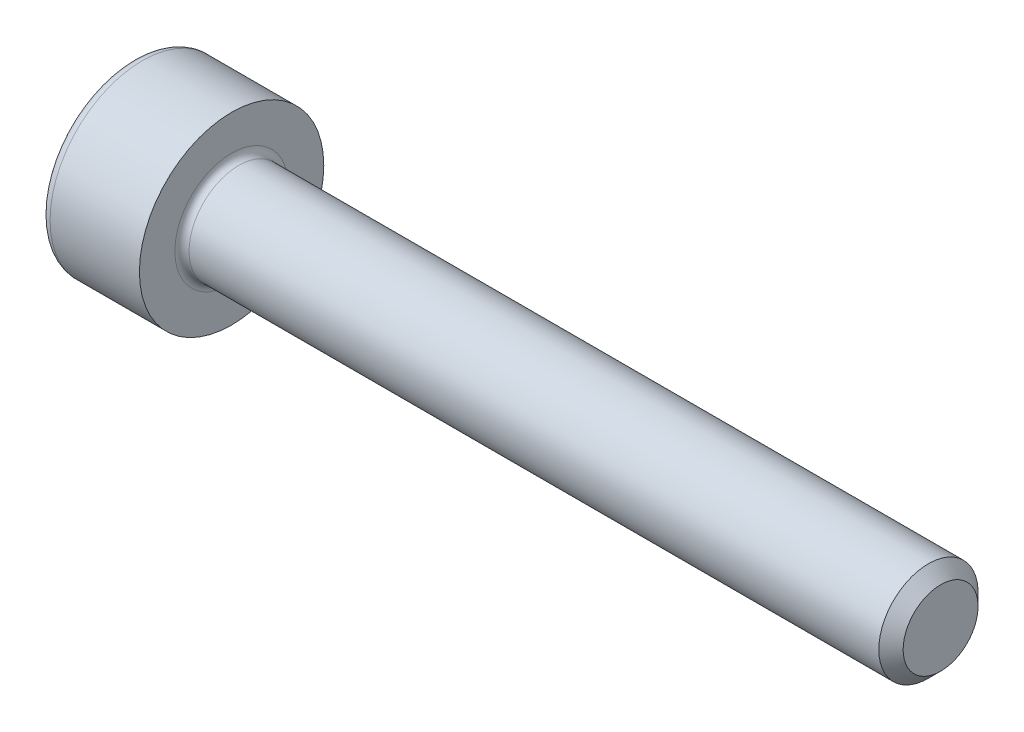
SolidWorks part; units mm, degrees
revolve "Base-Revolve" add sketch "BodySke"
sketch "BodySke" plane through (0, 0, 0) normal (0, 0, 1) x (1, 0, 0)
  line L0 (0, 0) -> (0, 1.3)
  line L1 (0, 1.3) -> (1.4, 1.3)
  line L2 (1.4, 1.3) -> (1.4, 0.7)
  line L3 (1.4, 0.7) -> (11.2285, 0.7)
  line L4 (11.4, 0.5285) -> (11.4, 0)
  line L5 (11.4, 0) -> (0, 0)
  line L6 (-31.75, 0) -> (127, 0) construction
  line L8 (11.4, 0.5285) -> (11.2285, 0.7)
  line L10 (11.4, -0.5285) -> (11.2285, -0.7) construction
  line L11 (1.7, 9.525) -> (1.7, 3.175) construction
  line L12 (1.4, 9.525) -> (1.4, 3.175) construction
  line L13 (-48.6, 9.525) -> (-48.6, 3.175) construction
  dimension "Head_ht" = 1.4
  dimension "Length" = 10
  dimension "Body_ch_ang" = 45
  dimension "Diameter" = 1.4
  dimension "Minor_dia" = 1.057
  dimension "Advance" = 0.3
  dimension "Thread_nom" = 10
  dimension "Thread_length" = 60
  dimension "Head_dia" = 2.6
cosmetic thread "ThreadCosmetic" [suppressed]
fillet "Fillet1" radius 0.1 1 edges at (1.4, 0, 0.7)
fillet "Fillet2" radius 0.14 1 edges at (0, 0, 1.3)
ref_plane "Plane1" through (0, 0, 0) normal (0, 0, 1) x (1, 0, 0)
ref_plane "Plane2" through (0, 0, 0) normal (0, 1, 0) x (1, 0, 0)
ref_plane "Plane3" through (0, 0, 0) normal (1, 0, 0) x (0, 0, -1)
sketch "Sketch2" plane through (0, 0, 0) normal (0, 0, 1) x (1, 0, 0)
  line L0 (0, 0.66) -> (0.6, 0.66)
  line L1 (0.6, 0.66) -> (0.9811, 0)
  line L2 (-31.75, 0) -> (127, 0) construction
  line L3 (0.9811, 0) -> (0, 0)
  line L4 (0, 0) -> (0, 0.66)
  line L6 (0, 0) -> (47.625, 0) construction
  dimension "D1" = 0.66
  dimension "D2" = 60
  dimension "Depth" = 0.6
revolve "Hex-PreBroach" cut sketch "Sketch2" angle 360 about L6
sketch "Sketch3" plane through (0, 0, 0) normal (-1, 0, 0) x (0, 0.5, 0.866)
  line L0 (0.3811, 0.66) -> (-0.3811, 0.66)
  line L1 (-0.3811, 0.66) -> (-0.7621, 0)
  line L2 (0.3811, 0.66) -> (0.7621, 0)
  line L3 (0.3811, -0.66) -> (0.7621, 0)
  line L4 (0.3811, -0.66) -> (-0.3811, -0.66)
  line L5 (-0.3811, -0.66) -> (-0.7621, 0)
  dimension "D1" = 0.66
  dimension "D2" = 0.66
  dimension "Hex_size" = 1.32
extrude "Hex" cut sketch "Sketch3" against normal blind 0.6
sketch "ThdSchSke" plane through (0, 0, 0) normal (0, 0, 1) x (1, 0, 0)
  line L0 (2.3, -0.5285) -> (2.1799, -0.7)
  line L1 (2.3, -0.5285) -> (2.4201, -0.7)
  line L2 (2.4201, -0.7) -> (2.4201, -0.875)
  line L3 (-3.175, 0) -> (5.1513, 0) construction
  line L4 (0, 1.16) -> (0, -1.16) construction
  line L5 (2.4201, -0.875) -> (2.1799, -0.875)
  line L6 (2.1799, -0.875) -> (2.1799, -0.7)
  dimension "Thread_minor" = 1.057
  dimension "Diameter" = 1.4
  dimension "Start" = 2.3
revolve "ThreadSchematic" [suppressed] cut sketch "ThdSchSke" angle 360 about L3
pattern_linear "ThdSchPat" [suppressed]
equation "\"D2@Sketch3\" = \"Hex_size@Sketch3\" / 2"
equation "\"D1@Sketch3\" = \"Hex_size@Sketch3\" / 2"
equation "\"D1@Sketch2\" = \"Hex_size@Sketch3\" / 2"
equation "\"Thread_minor@ThreadCosmetic\"  =  \"Minor_dia@BodySke\""
equation "\"Depth@Sketch2\" =  \"Key_eng@Hex\""
equation "\"Thread_length@ThreadCosmetic\" = ((sgn( (\"Length@BodySke\" - \"Advance@BodySke\" * 3.0) - \"Thread_nom@BodySke\" )-1)*( (\"Length@BodySke\" - \"Advance@BodySke\" * 3.0) - \"Thread_nom@BodySke\" ))/-2+ \"Thread_nom@BodySke\""
equation "\"Thread_minor@ThdSchSke\" = \"Minor_dia@BodySke\""
equation "\"Diameter@ThdSchSke\" = \"Diameter@BodySke\""
equation "\"Overcut@ThdSchSke\" = \"Diameter@BodySke\" * 1.25"
equation "\"Start@ThdSchSke\" = \"Head_ht@BodySke\" + \"Length@BodySke\" - \"Thread_length@ThreadCosmetic\"  '---Non-countersunk---"
equation "\"Num_threads@ThdSchPat\" = int( \"Thread_length@ThreadCosmetic\" / \"Advance@BodySke\" + 0.999 )  + 1"
equation "\"Advance@ThdSchPat\" = \"Thread_length@ThreadCosmetic\" /  (\"Num_threads@ThdSchPat\" - 1) 'relax it"
equation "\"Num_threads@ThdSchPat\" = \"Num_threads@ThdSchPat\" - sgn( \"Num_threads@ThdSchPat\" - 1) '---chamfered tips only---"
